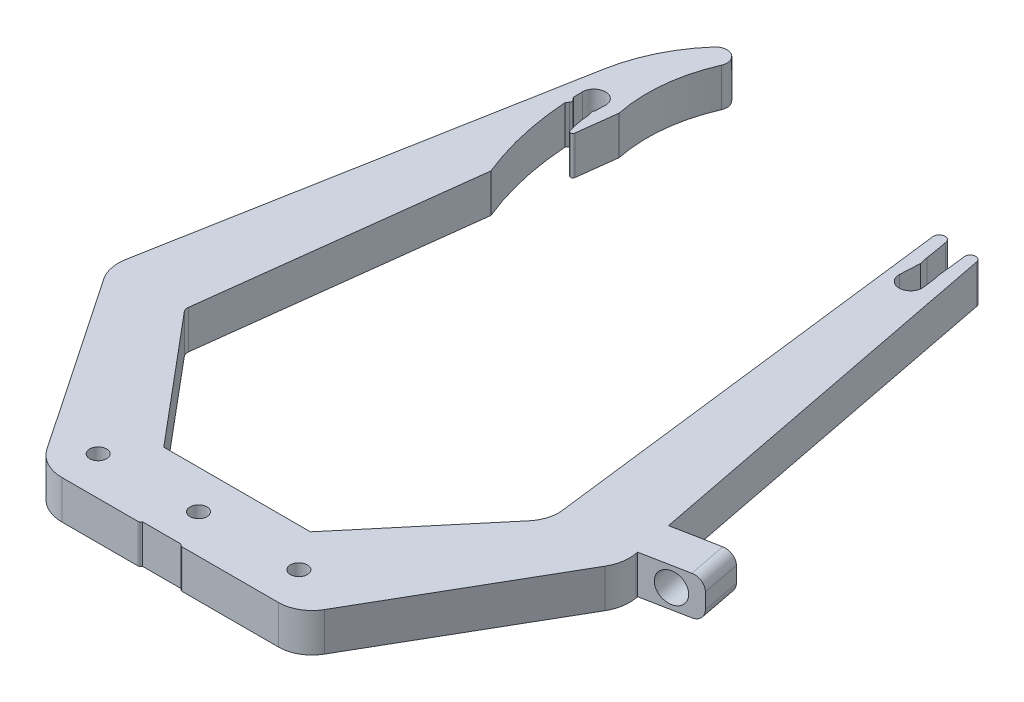
SolidWorks part; units mm, degrees
ref_plane "前视基准面" through (0, 0, 0) normal (0, 0, 1) x (1, 0, 0)
ref_plane "上视基准面" through (0, 0, 0) normal (0, 1, 0) x (1, 0, 0)
ref_plane "右视基准面" through (0, 0, 0) normal (1, 0, 0) x (0, 0, -1)
sketch "草图1" plane through (0, 0, 0) normal (0, 1, 0) x (1, 0, 0)
  line L0 (0, 0) -> (0, -20) construction
  line L1 (-19, 0) -> (19, 0)
  line L2 (-35.7227, -20) -> (35.7227, -20) construction
  line L3 (19, 0) -> (44.8546, 30.8123)
  line L4 (46.8223, 37.4552) -> (33.3895, 146.8562)
  line L5 (38.2306, -15.6563) -> (64.8605, 30.468)
  line L6 (66.0165, 37.3761) -> (44.728, 146.8959)
  line L7 (-5, -19.5) -> (5, -19.5)
  line L8 (5, -19.5) -> (5.3536, -19.8536)
  line L9 (5.7071, -20) -> (30.7071, -20)
  line L10 (-5, -19.5) -> (-5.3536, -19.8536)
  line L11 (-5.7071, -20) -> (-25.3998, -20)
  line L12 (-35.7227, -20) -> (-64.8605, 30.468) construction
  line L13 (-19, 0) -> (-46.7237, 33.0398)
  line L14 (-47.2827, 33.706) -> (-33.3895, 146.8562) construction
  line L15 (-66.0165, 37.3761) -> (-46.8296, 141.8909)
  line L18 (-34.9739, 133.9531) -> (-47.1767, 34.5691)
  line L44 (-64.8605, 30.468) -> (-33.6816, -15.6046)
  line L45 (43.5031, 134.5037) -> (43.077, 137.8137)
  line L46 (42.1293, 145.1753) -> (42.8054, 138.9383)
  line L47 (42.8076, 138.9256) -> (43.077, 137.8137)
  line L48 (37.3208, 141.4732) -> (37.8151, 139.2584)
  line L49 (42.1293, 145.1753) -> (41.9652, 146.45)
  line L50 (37.8174, 139.2316) -> (37.5579, 134.1048)
  arc A0 (64.8605, 30.468) -> (66.0165, 37.3761) centre (56.2002, 35.468) ccw
  arc A1 (-64.8605, 30.468) -> (-66.0165, 37.3761) centre (-56.2002, 35.468) cw
  arc A2 (33.3895, 146.8562) -> (36.3769, 147.1048) centre (34.8784, 147.039) cw
  arc A4 (37.5579, 134.1048) -> (43.5031, 134.5037) centre (40.5541, 133.9531) ccw
  arc A5 (44.728, 146.8959) -> (41.9652, 146.45) centre (43.3537, 146.6287) ccw
  arc A7 (-46.8296, 141.8909) -> (-37.4802, 161.1337) centre (-7.4871, 134.6684) cw
  arc A8 (-37.4802, 161.1337) -> (-32.4793, 157.9531) centre (-35.2307, 159.1488) cw
  arc A9 (-32.4793, 157.9531) -> (-34.9739, 133.9531) centre (4.2063, 142.0103) ccw
  arc A10 (-46.7237, 33.0398) -> (-47.1767, 34.5691) centre (-45.1916, 34.3254) cw
  arc A19 (38.2306, -15.6563) -> (30.7071, -20) centre (30.7071, -11.3127) cw
  arc A20 (44.8546, 30.8123) -> (46.8223, 37.4552) centre (38.1997, 36.3964) ccw
  arc A21 (5.3536, -19.8536) -> (5.7071, -20) centre (5.7071, -19.5) ccw
  arc A22 (-5.3536, -19.8536) -> (-5.7071, -20) centre (-5.7071, -19.5) cw
  arc A34 (-25.3998, -20) -> (-33.6816, -15.6046) centre (-25.3998, -10) cw
  arc A37 (42.8054, 138.9383) -> (42.8076, 138.9256) centre (42.9048, 138.9491) ccw
  arc A38 (37.8151, 139.2584) -> (37.8174, 139.2316) centre (37.7175, 139.2366) cw
  arc A39 (36.3769, 147.1048) -> (37.3208, 141.4732) centre (-54.0014, 129.0619) cw
  point P7 (0, 0)
  point P9 (0, -20)
  point P18 (66.7299, 33.706)
  point P24 (0, -19.5)
  point P43 (-30.7071, -20)
  point P50 (46.8296, 141.8909)
  point P53 (42.8061, 138.9319)
  point P76 (-42.7886, -7.7616)
  point P85 (47.2827, 33.706)
  point P88 (5.5, -20)
  point P91 (-5.5, -20)
  dimension "D14" = 10
  dimension "D17" = 1.5
  dimension "D18" = 3
  dimension "1.4" = 1.4
  dimension "D23" = 40
  dimension "D24" = 3
  dimension "D26" = 40
  dimension "D30" = 2
  dimension "D39" = 0.5
  dimension "D28" = 10
  dimension "D15" = 4.8
  dimension "D16" = 0.1
  dimension "D1" = 20
  dimension "D2" = 38
  dimension "D4" = 130
  dimension "D5" = 44
  dimension "D6" = 133
  dimension "D7" = 114
  dimension "D8" = 120
  dimension "D9" = 139
  dimension "D10" = 110
  dimension "D11" = 5
  dimension "D12" = 1
  dimension "D13" = 135
  dimension "D19" = 13
  dimension "D25" = 13
  dimension "D27" = 24
  dimension "D29" = 25
  dimension "D31" = 25
extrude "凸台-拉伸1" add sketch "草图1" along normal blind 10
sketch "草图2" plane through (0, 10, 0) normal (0, 1, 0) x (1, 0, 0)
  line L0 (-47.1767, 34.5691) -> (-34.9739, 133.9531) construction
  line L2 (-36.5496, 121.12) -> (-38.6077, 104.3574)
  line L4 (-38.7444, 130.4462) -> (-38.4867, 129.7939)
  line L9 (40.5541, 133.9531) -> (-57.9515, 133.9531) construction
  line L10 (0, 0) -> (0, -21.5487) construction
  line L11 (-38.5563, 131.3155) -> (-38.5461, 131.3251)
  line L12 (-44.4474, 131.5436) -> (-43.9248, 131.0031)
  line L13 (-43.8451, 129.9874) -> (-44.3325, 129.293)
  line L14 (38.654, -10) -> (-42.7555, -10) construction
  line L15 (19, 0) -> (-19, 0) construction
  arc A0 (-38.6077, 104.3574) -> (-44.3325, 129.293) centre (35.4981, 134.4958) cw
  circle A3 centre (0, -10) radius 2.2
  arc A7 (-38.5057, 133.7686) -> (-38.5563, 131.3155) centre (-8.5625, 131.9238) ccw
  arc A13 (-38.5057, 133.7686) -> (-44.4999, 133.932) centre (-41.5, 133.9531) ccw
  arc A14 (-44.4474, 131.5436) -> (-44.4999, 133.932) centre (35.4981, 134.4958) cw
  arc A15 (-38.4867, 129.7939) -> (-36.5496, 121.12) centre (-8.5625, 131.9238) ccw
  arc A16 (-38.5461, 131.3251) -> (-38.7444, 130.4462) centre (-38.0003, 130.7401) ccw
  arc A17 (-43.9248, 131.0031) -> (-43.8451, 129.9874) centre (-44.4999, 130.447) cw
  circle A18 centre (-26, -10) radius 2.2
  circle A19 centre (26, -10) radius 2.2
  point P30 (-38.9446, 130.9532)
  point P32 (-38.4181, 119.1092)
  point P34 (-43.4656, 130.5282)
  dimension "D5" = 3
  dimension "D6" = 30
  dimension "D7" = 80
  dimension "D9" = 4.4
  dimension "D11" = 26
  dimension "D12" = 0.8
  dimension "D14" = 10
  dimension "D2" = 4.4
  dimension "D3" = 4.4
  dimension "D4" = 41.5
  dimension "D13" = 26
extrude "切除-拉伸1" cut sketch "草图2" against normal up to next
fillet "圆角1" radius 0.6 2 edges at (-34.9739, 5, -133.9531) (-36.5496, 5, -121.12)
sketch "草图3" plane through (70.6136, 0, -13.7259) normal (0.9816, 0, -0.1908) x (-0.1908, 0, -0.9816)
  line L0 (24.0929, 10) -> (135.6625, 10) construction
  line L1 (24.5438, 10) -> (34.6883, 10)
  line L2 (24.5438, 10) -> (24.5438, 0)
  line L3 (24.5438, 0) -> (34.6883, 0)
  line L4 (34.6883, 10) -> (34.6883, 0)
  line L5 (24.0929, 0) -> (135.6625, 0) construction
extrude "凸台-拉伸2" add sketch "草图3" along normal blind 15
sketch "草图4" plane through (-4.6832, 0, -24.0929) normal (0.1908, 0, 0.9816) x (0.9816, 0, -0.1908)
  line L0 (86.9353, 5) -> (71.9353, 5) construction
  line L1 (86.9353, 10) -> (86.9353, 0) construction
  line L2 (71.9353, 10) -> (71.9353, 0) construction
  circle A0 centre (79.4353, 5) radius 3.8
  dimension "D1" = 7.6
extrude "切除-拉伸2" cut sketch "草图4" against normal up to next
fillet "圆角2" radius 3 2 edges at (79.687, 0, -45.66) (79.687, 10, -45.66)
